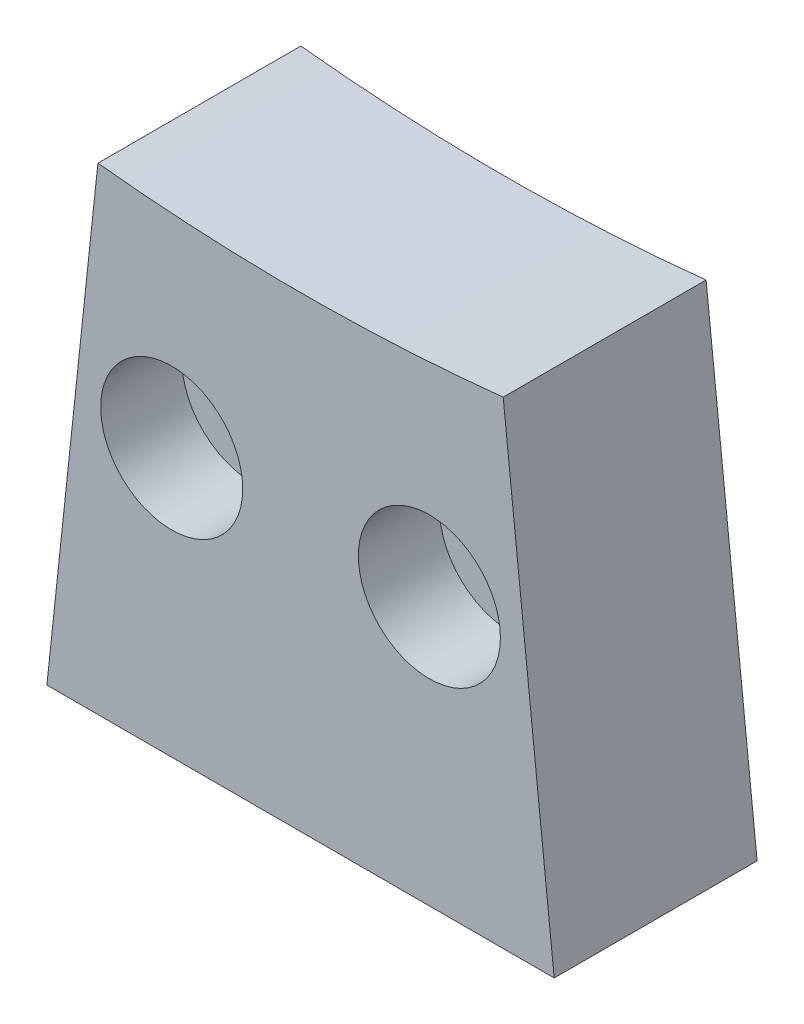
SolidWorks part; units mm, degrees
ref_plane "Plan de face" through (0, 0, 0) normal (0, 0, 1) x (1, 0, 0)
ref_plane "Plan de dessus" through (0, 0, 0) normal (0, 1, 0) x (1, 0, 0)
ref_plane "Plan de droite" through (0, 0, 0) normal (1, 0, 0) x (0, 0, -1)
sketch "Esquisse1" plane through (0, 0, 0) normal (0, 0, 1) x (1, 0, 0)
  line L0 (0, 0) -> (0, -117) construction
  line L1 (0, 0) -> (-9.9859, -93.4681) construction
  line L2 (0, 0) -> (9.9859, -93.4681) construction
  line L3 (-12.5, -117) -> (12.5, -117)
  line L4 (-9.9859, -93.4681) -> (-12.5, -117)
  line L5 (9.9859, -93.4681) -> (12.5, -117)
  arc A1 (9.9859, -93.4681) -> (-9.9859, -93.4681) centre (0, 0) cw
  point P1 (0, -94)
  point P8 (0, -117)
  dimension "D1" = 94
  dimension "D2" = 117
  dimension "D3" = 25
extrude "Boss.-Extru.1" add sketch "Esquisse1" along normal blind 10
sketch "Esquisse2" plane through (0, -117, 0) normal (0, -1, 0) x (1, 0, 0)
  line L0 (-4.75, 6) -> (4.75, 6) construction
  line L1 (-12.5, 10) -> (12.5, 10) construction
  circle A0 centre (-4.75, 6) radius 1.025
  circle A1 centre (4.75, 6) radius 1.025
  point P4 (0, 6)
  point P7 (0, 10)
  dimension "D1" = 2.05
  dimension "D2" = 9.5
  dimension "D3" = 4
extrude "Enlèv. mat.-Extru.1" cut sketch "Esquisse2" against normal blind 8
sketch "Esquisse3" plane through (0, 0, 10) normal (0, 0, 1) x (1, 0, 0)
  line L0 (0, -94) -> (0, -117) construction
  line L1 (-12.5, -117) -> (12.5, -117) construction
  line L2 (-6.349, -103.806) -> (0, 0) construction
  line L3 (0, 0) -> (6.349, -103.806) construction
  arc A0 (6.349, -103.806) -> (-6.349, -103.806) centre (0, 0) cw construction
  circle A1 centre (-6.349, -103.806) radius 1.75
  circle A2 centre (6.349, -103.806) radius 1.75
  arc A3 (-9.9859, -93.4681) -> (9.9859, -93.4681) centre (0, 0) ccw construction
  point P13 (0, -104)
  dimension "D1" = 104
  dimension "D2" = 3.5
  dimension "D3" = 7
extrude "Enlèv. mat.-Extru.2" cut sketch "Esquisse3" against normal up to next
sketch "Esquisse4" plane through (0, 0, 10) normal (0, 0, 1) x (1, 0, 0)
  circle A0 centre (-6.349, -103.806) radius 3.5
  circle A1 centre (6.349, -103.806) radius 3.5
  circle M4 centre (6.349, -103.806) radius 1.75
  dimension "D1" = 7
extrude "Enlèv. mat.-Extru.3" cut sketch "Esquisse4" against normal blind 4 contours A1 M4 | A0
